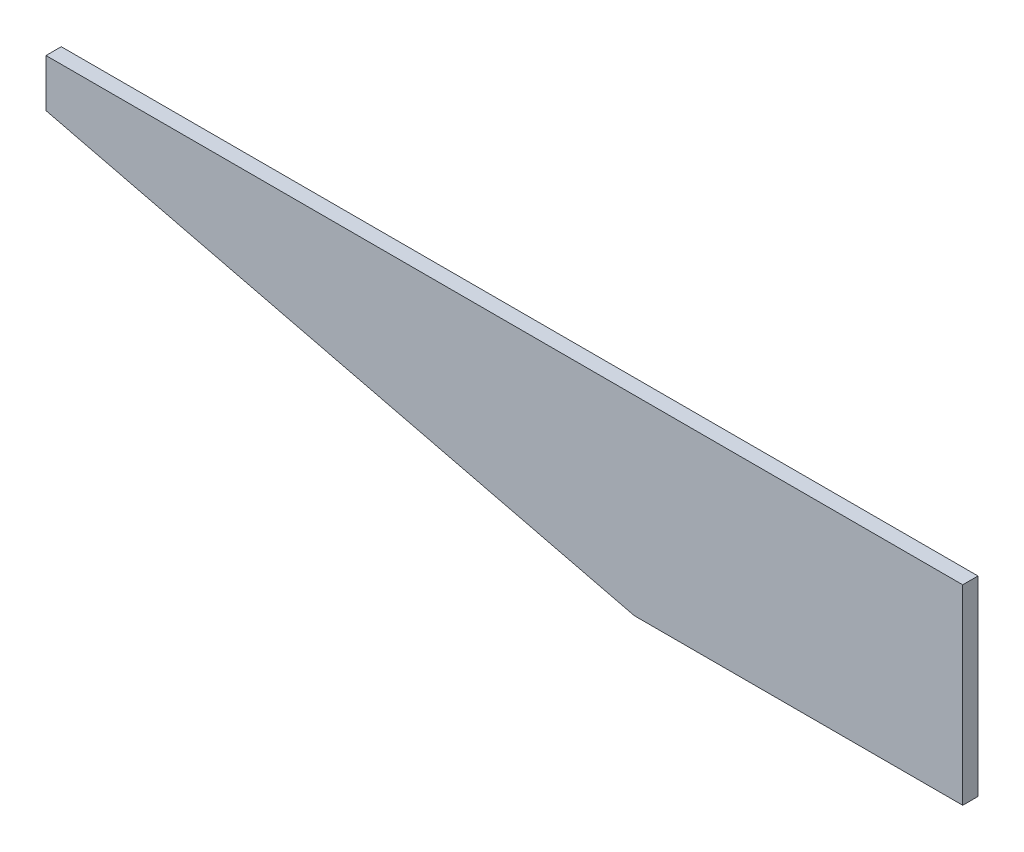
SolidWorks part; units mm, degrees
ref_plane "Plan de face" through (0, 0, 0) normal (0, 0, 1) x (1, 0, 0)
ref_plane "Plan de dessus" through (0, 0, 0) normal (0, 1, 0) x (1, 0, 0)
ref_plane "Plan de droite" through (0, 0, 0) normal (1, 0, 0) x (0, 0, -1)
sketch "Esquisse1" plane through (0, 0, 0) normal (0, 0, 1) x (1, 0, 0)
  line L0 (-600, 0) -> (0, 0) construction
  line L1 (-600, 0) -> (0, 0)
  line L2 (0, 0) -> (0, -125)
  line L3 (0, -125) -> (-215, -125)
  line L4 (-215, -125) -> (-600, -31.25)
  line L5 (-600, -31.25) -> (-600, 0)
  dimension "D1" = 125
  dimension "D2" = 215
  dimension "D3" = 31.25
extrude "Boss.-Extru.1" add sketch "Esquisse1" against normal blind 10
